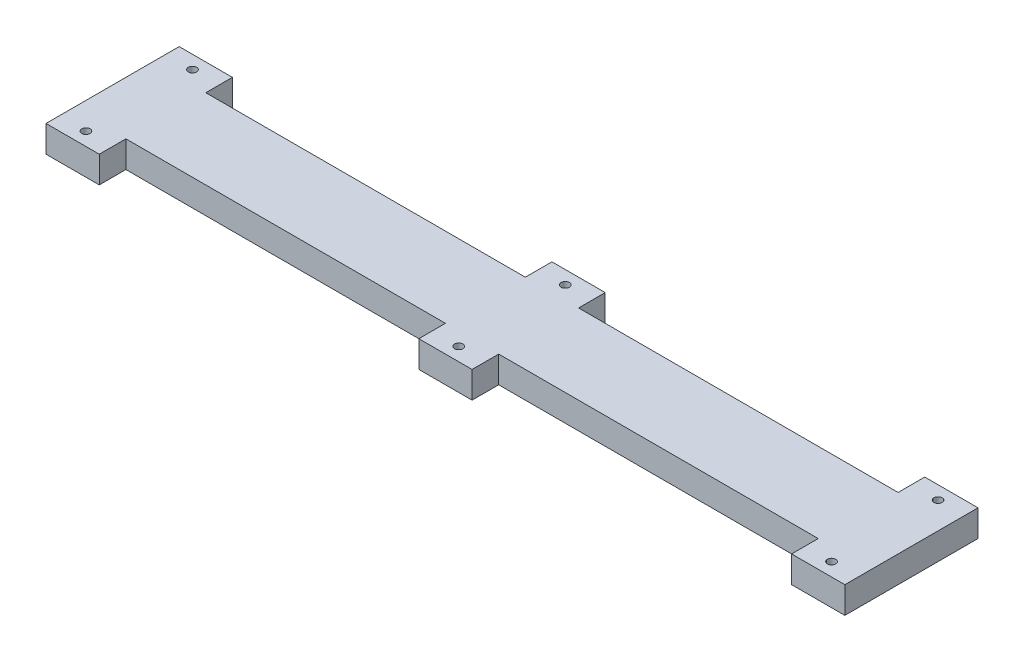
SolidWorks part; units mm, degrees
ref_plane "Ön Düzlem" through (0, 0, 0) normal (0, 0, 1) x (1, 0, 0)
ref_plane "Üst Düzlem" through (0, 0, 0) normal (0, 1, 0) x (1, 0, 0)
ref_plane "Sağ Düzlem" through (0, 0, 0) normal (1, 0, 0) x (0, 0, -1)
sketch "Çizim1" plane through (0, 0, 0) normal (0, 1, 0) x (1, 0, 0)
  line L1 (-150, -25) -> (150, -25)
  line L2 (-150, -25) -> (-150, 25)
  line L3 (-150, 25) -> (150, 25)
  line L4 (150, -25) -> (150, 25)
  line L5 (-150, -25) -> (150, 25) construction
  line L6 (-150, 25) -> (150, -25) construction
  point P0 (0, 0)
extrude "Yükseklik-Ekstrüzyon1" add sketch "Çizim1" along normal blind 10
sketch "Çizim2" plane through (0, 10, 0) normal (0, 1, 0) x (1, 0, 0)
  line L0 (-130, -25) -> (-10, -25)
  line L1 (-130, -25) -> (-130, -15)
  line L2 (-10, -25) -> (-10, -15)
  line L3 (-130, -15) -> (-10, -15)
  line L4 (-150, -25) -> (150, -25) construction
  line L5 (-150, 25) -> (-150, -25) construction
  line L6 (10, -25) -> (10, -15)
  line L7 (10, -25) -> (130, -25)
  line L8 (10, -15) -> (130, -15)
  line L9 (130, -25) -> (130, -15)
  line L10 (-130, 25) -> (-10, 25)
  line L11 (-130, 25) -> (-130, 15)
  line L12 (-10, 25) -> (-10, 15)
  line L13 (-130, 15) -> (-10, 15)
  line L14 (150, 25) -> (-150, 25) construction
  line L15 (10, 25) -> (10, 15)
  line L16 (10, 25) -> (130, 25)
  line L17 (10, 15) -> (130, 15)
  line L18 (130, 25) -> (130, 15)
  line L19 (150, -25) -> (150, 25) construction
  circle A0 centre (140, 20) radius 1.55
  circle A1 centre (0, 20) radius 1.55
  circle A2 centre (-140, 20) radius 1.55
  circle A3 centre (0, -20) radius 1.55
  circle A4 centre (-140, -20) radius 1.55
  circle A5 centre (140, -20) radius 1.55
  dimension "D8" = 10
  dimension "D10" = 3
  dimension "D1" = 20
  dimension "D2" = 20
  dimension "D3" = 20
  dimension "D4" = 20
  dimension "D5" = 120
  dimension "D6" = 120
  dimension "D7" = 20
  dimension "D9" = 5
  dimension "D11" = 2
extrude "Kes-Ekstrüzyon1" cut sketch "Çizim2" against normal blind 10
